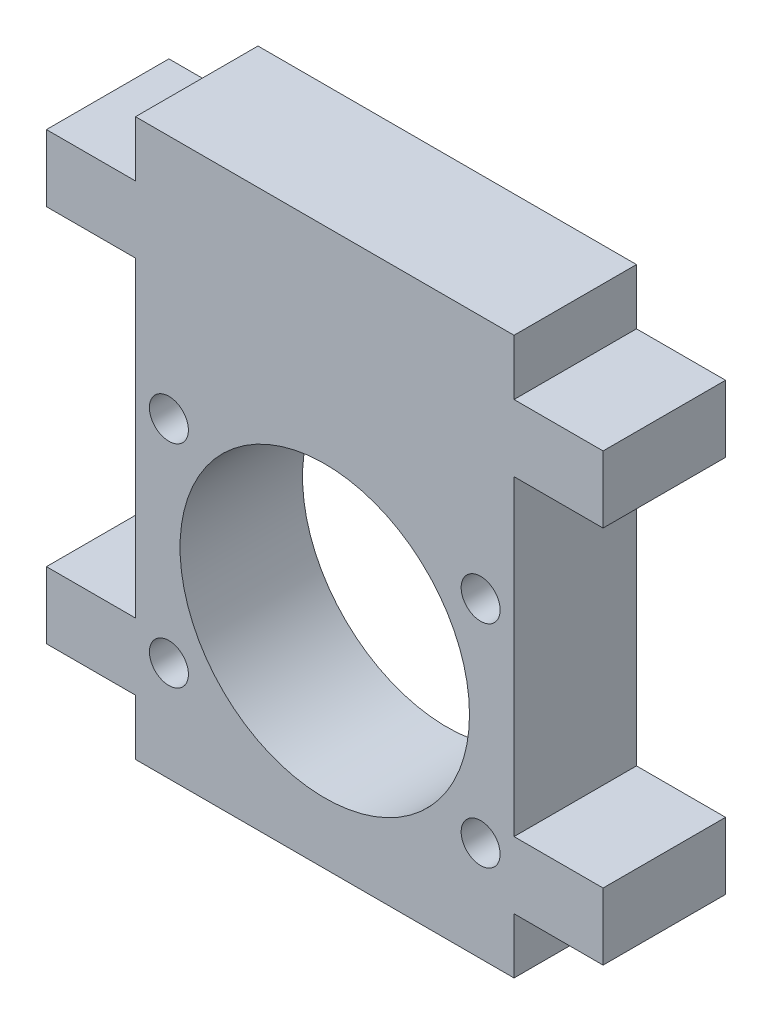
SolidWorks part; units mm, degrees
ref_plane "Plan de face" through (0, 0, 0) normal (0, 0, 1) x (1, 0, 0)
ref_plane "Plan de dessus" through (0, 0, 0) normal (0, 1, 0) x (1, 0, 0)
ref_plane "Plan de droite" through (0, 0, 0) normal (1, 0, 0) x (0, 0, -1)
sketch "Esquisse1" plane through (0, 0, 0) normal (0, 0, 1) x (1, 0, 0)
  line L0 (17, 29) -> (17, 0) construction
  line L1 (0, 0) -> (34, 0) construction
  line L2 (0, 0) -> (0, 25) construction
  line L3 (0, 25) -> (34, 25) construction
  line L4 (34, 0) -> (34, 25) construction
  line L5 (34, 13.5) -> (0, 13.5) construction
  line L6 (3, 25) -> (3, 0) construction
  line L7 (31, 25) -> (31, 0) construction
  line L8 (0, 25) -> (0, 6)
  line L9 (0, 6) -> (-8, 6)
  line L10 (-8, 6) -> (-8, 0)
  line L11 (-8, 0) -> (0, 0)
  line L12 (0, 0) -> (0, -5)
  line L13 (0, -5) -> (34, -5)
  line L14 (34, -5) -> (34, 0)
  line L15 (34, 0) -> (42, 0)
  line L16 (42, 0) -> (42, 6)
  line L17 (42, 6) -> (34, 6)
  line L18 (34, 6) -> (34, 25)
  line L19 (34, 25) -> (34, 34)
  line L20 (34, 34) -> (42, 34)
  line L21 (42, 34) -> (42, 40)
  line L22 (42, 40) -> (34, 40)
  line L23 (34, 40) -> (34, 45)
  line L24 (34, 45) -> (0, 45)
  line L25 (0, 45) -> (0, 40)
  line L26 (0, 40) -> (-8, 40)
  line L27 (-8, 40) -> (-8, 34)
  line L28 (-8, 34) -> (0, 34)
  line L29 (0, 34) -> (0, 25)
  circle A0 centre (17, 13.5) radius 13
  circle A1 centre (3, 23) radius 1.75
  circle A2 centre (31, 23) radius 1.75
  circle A3 centre (31, 4) radius 1.75
  circle A4 centre (3, 4) radius 1.75
  dimension "D6" = 3.5
  dimension "D16" = 26
  dimension "D2" = 25
  dimension "D3" = 34
  dimension "D4" = 5
  dimension "D5" = 19
  dimension "D9" = 15
  dimension "D10" = 6
  dimension "D11" = 8
  dimension "D12" = 5
  dimension "D13" = 6
  dimension "D14" = 3
  dimension "D15" = 13.5
  dimension "D17" = 40
  dimension "D7" = 2
  dimension "D8" = 2
extrude "Boss.-Extru.1" add sketch "Esquisse1" along normal blind 11
